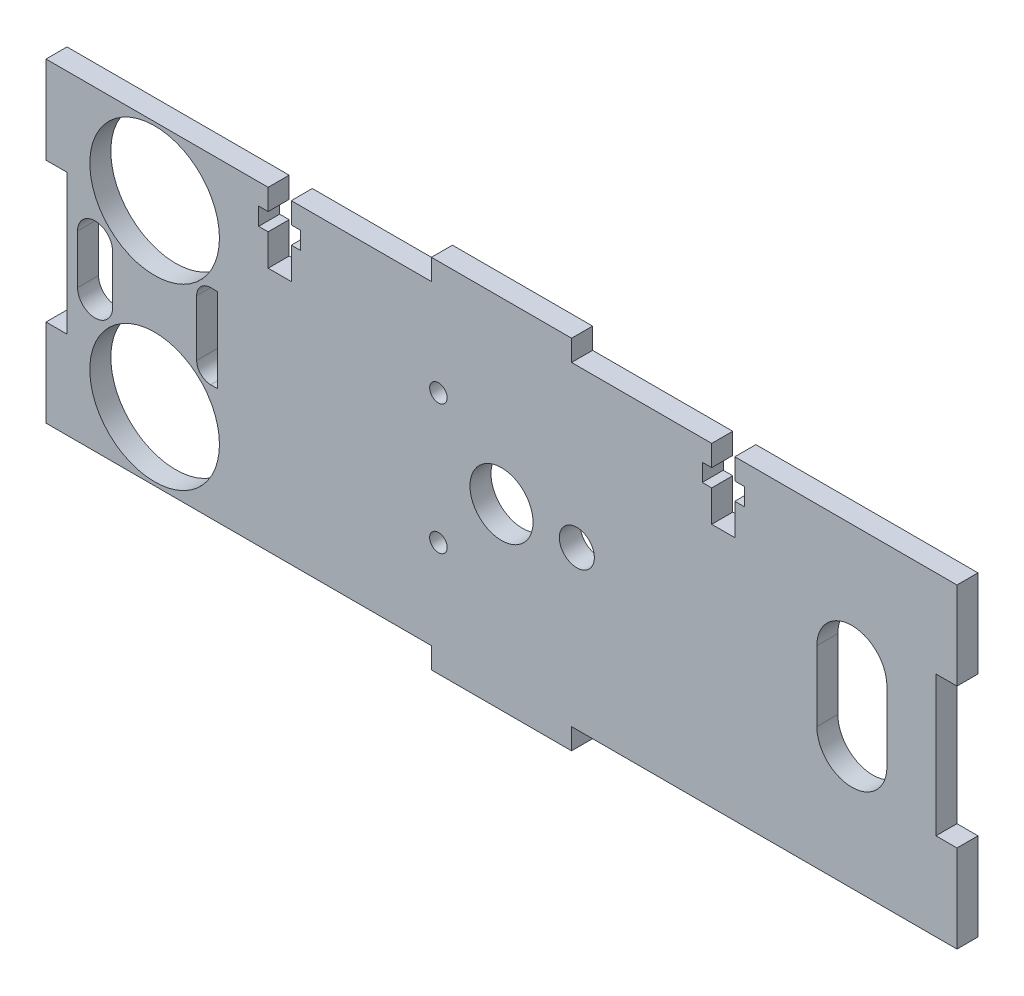
SolidWorks part; units mm, degrees
ref_plane "Front Plane" through (0, 0, 0) normal (0, 0, 1) x (1, 0, 0)
ref_plane "Top Plane" through (0, 0, 0) normal (0, 1, 0) x (1, 0, 0)
ref_plane "Right Plane" through (0, 0, 0) normal (1, 0, 0) x (0, 0, -1)
sketch "Sketch1" plane through (0, 0, 0) normal (0, 0, 1) x (1, 0, 0)
  line L0 (-10, -22.5) -> (-65, -22.5)
  line L1 (65, -22.5) -> (10, -22.5)
  line L2 (65, -22.5) -> (65, -10)
  line L3 (65, 22.5) -> (33.3, 22.5)
  line L4 (-65, -22.5) -> (-65, -10)
  line L5 (65, -22.5) -> (-65, 22.5) construction
  line L6 (65, 22.5) -> (-65, -22.5) construction
  line L8 (-10, -22.5) -> (-10, -25.5)
  line L9 (-10, -25.5) -> (10, -25.5)
  line L10 (10, -22.5) -> (10, -25.5)
  line L11 (0, -55) -> (0, 55) construction
  line L12 (-62, -10) -> (-65, -10)
  line L13 (-62, -10) -> (-62, 10)
  line L14 (-62, 10) -> (-65, 10)
  line L16 (-62, -10) -> (-65, 10) construction
  line L17 (-62, 10) -> (-65, -10) construction
  line L18 (62, 10) -> (65, 10)
  line L20 (62, -10) -> (65, -10)
  line L21 (62, -10) -> (62, 10)
  line L22 (-65, 10) -> (-65, 22.5)
  line L23 (65, 10) -> (65, 22.5)
  line L24 (-58, 3.5) -> (-58, -3.5) construction
  line L29 (-55.5, 3.5) -> (-55.5, -3.5)
  line L30 (-60.5, 3.5) -> (-60.5, -3.5)
  line L31 (-40.5, -6) -> (-41.5, -6)
  line L32 (-40.5, -6) -> (-40.5, 6)
  line L33 (-40.5, 6) -> (-41.5, 6)
  line L34 (-43.5, -4) -> (-43.5, 4)
  line L35 (-40.5, -6) -> (-43.5, 6) construction
  line L36 (-40.5, 6) -> (-43.5, -6) construction
  line L37 (55, 0) -> (-55, 0) construction
  line L40 (-10, 22.5) -> (-10, 25.5)
  line L41 (-10, 25.5) -> (10, 25.5)
  line L42 (10, 22.5) -> (10, 25.5)
  line L43 (-10, 22.5) -> (-30, 22.5)
  line L44 (33.3, 12.5) -> (30, 12.5)
  line L46 (-33.3, 22.5) -> (-33.3, 19.5)
  line L47 (-33.3, 12.5) -> (-30, 12.5)
  line L48 (-30, 22.5) -> (-30, 19.5)
  line L49 (-34.65, 19.5) -> (-33.3, 19.5)
  line L50 (-34.65, 19.5) -> (-34.65, 17)
  line L51 (-34.65, 17) -> (-33.3, 17)
  line L52 (-28.65, 19.5) -> (-28.65, 17)
  line L53 (30, 22.5) -> (30, 19.5)
  line L55 (33.3, 22.5) -> (33.3, 19.5)
  line L56 (34.65, 17) -> (33.3, 17)
  line L57 (28.65, 19.5) -> (28.65, 17)
  line L58 (34.65, 19.5) -> (33.3, 19.5)
  line L59 (34.65, 19.5) -> (34.65, 17)
  line L60 (-33.3, 22.5) -> (-65, 22.5)
  line L61 (-30, 19.5) -> (-28.65, 19.5)
  line L62 (-33.3, 17) -> (-33.3, 12.5)
  line L63 (-30, 17) -> (-28.65, 17)
  line L64 (-30, 17) -> (-30, 12.5)
  line L65 (30, 22.5) -> (10, 22.5)
  line L66 (30, 19.5) -> (28.65, 19.5)
  line L67 (30, 17) -> (30, 12.5)
  line L68 (33.3, 17) -> (33.3, 12.5)
  line L69 (30, 17) -> (28.65, 17)
  line L70 (50, -5) -> (50, 5) construction
  line L75 (45, -5) -> (45, 5)
  line L76 (55, -5) -> (55, 5)
  circle A0 centre (-49.5, 12.75) radius 9.25
  circle A1 centre (-49.5, -12.75) radius 9.25
  circle A6 centre (0, 0) radius 4.5
  circle A7 centre (10.75, 0) radius 2.5
  arc A10 (-55.5, 3.5) -> (-60.5, 3.5) centre (-58, 3.5) ccw
  arc A11 (-60.5, -3.5) -> (-55.5, -3.5) centre (-58, -3.5) ccw
  arc A12 (-41.5, -6) -> (-43.5, -4) centre (-41.5, -4) cw
  arc A13 (-41.5, 6) -> (-43.5, 4) centre (-41.5, 4) ccw
  circle A14 centre (-9, 9.25) radius 1.25
  circle A15 centre (-9, -9.25) radius 1.25
  arc A16 (45, -5) -> (55, -5) centre (50, -5) ccw
  arc A17 (55, 5) -> (45, 5) centre (50, 5) ccw
  point P0 (0, 0)
  point P10 (-63.5, 0)
  point P26 (-58, 0)
  point P49 (-42, 0)
  point P83 (50, 0)
  dimension "D8" = 18.5
  dimension "D15" = 2
  dimension "D16" = 9
  dimension "D17" = 5
  dimension "D22" = 2.5
  dimension "D12" = 2.5
  dimension "D35" = 5
  dimension "D1" = 130
  dimension "D2" = 45
  dimension "D3" = 3
  dimension "D4" = 20
  dimension "D5" = 55
  dimension "D6" = 20
  dimension "D7" = 3
  dimension "D9" = 15.5
  dimension "D10" = 25.5
  dimension "D11" = 12.75
  dimension "D13" = 7
  dimension "D14" = 6
  dimension "D18" = 10.75
  dimension "D19" = 3
  dimension "D20" = 12
  dimension "D21" = 6
  dimension "D23" = 9
  dimension "D24" = 9.25
  dimension "D25" = 20
  dimension "D26" = 3
  dimension "D27" = 55
  dimension "D28" = 3.3
  dimension "D29" = 10
  dimension "D30" = 2.5
  dimension "D31" = 6
  dimension "D32" = 3
  dimension "D33" = 1.35
  dimension "D34" = 20
  dimension "D36" = 10
  dimension "D37" = 10
extrude "Boss-Extrude1" add sketch "Sketch1" along normal blind 3
